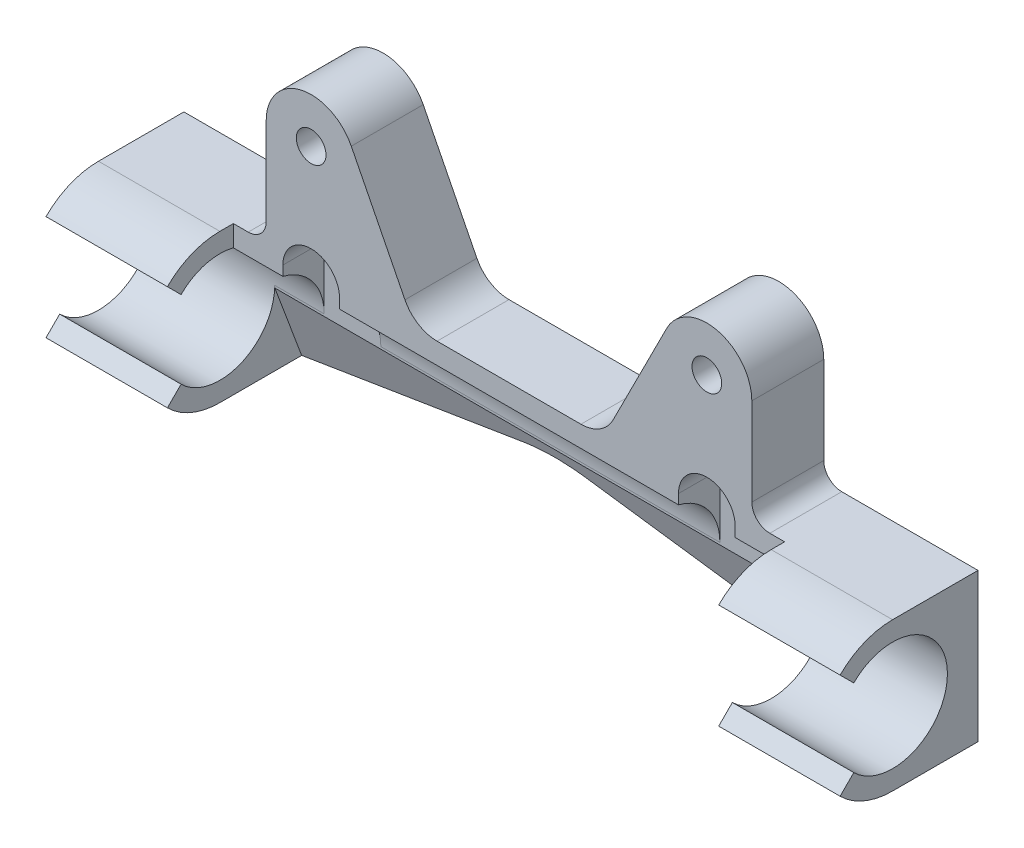
SolidWorks part; units mm, degrees
ref_plane "Front Plane" through (0, 0, 0) normal (0, 0, 1) x (1, 0, 0)
ref_plane "Top Plane" through (0, 0, 0) normal (0, 1, 0) x (1, 0, 0)
ref_plane "Right Plane" through (0, 0, 0) normal (1, 0, 0) x (0, 0, -1)
sketch "Sketch1" plane through (0, 0, 0) normal (-1, 0, 0) x (0, 0, 1)
  line L0 (-9.5, 8.25) -> (-9.5, -8.25)
  line L1 (0, 8.25) -> (-9.5, 8.25)
  line L2 (0, -8.25) -> (-9.5, -8.25)
  arc A4 (0, -8.25) -> (0, 8.25) centre (0, 0) ccw
  dimension "D2" = 16.5
  dimension "D3" = 9.5
extrude "Boss-Extrude1" add sketch "Sketch1" along normal blind 88.3
hole_wizard "Ø2.7 (2.7) Diameter Hole1" [suppressed] positions "Sketch5" profile "Sketch4" hole size "Ø2.7" standard "Ansi Metric"
sketch "Sketch5" [suppressed] plane through (-9.5, 0, 0) normal (-1, 0, 0) x (0, 0, 1)
  line L1 (2.5, -5) -> (11, -5) construction
  line L2 (2.5, -5) -> (2.5, 5) construction
  line L3 (2.5, 5) -> (11, 5) construction
  line L4 (11, -5) -> (11, 5) construction
  line L5 (0, 0) -> (2.5, 0) construction
  line L7 (-8.25, 0) -> (8.25, 0) construction
  line L10 (13.5, 0) -> (11, 0) construction
  line L11 (-8.25, 13.5) -> (8.25, 13.5) construction
  point P0 (2.5, -5)
  point P89 (2.5, 5)
  point P91 (11, 5)
  point P93 (11, -5)
  dimension "D1" = 2.5
  dimension "D2" = 10
sketch "Sketch4" plane through (-9.5, -5, 2.5) normal (0, 1, 0) x (0, 0, 1)
  line L0 (0, 0) -> (0, 4.8112)
  line L1 (0, 4.8112) -> (1.35, 4)
  line L2 (1.35, 4) -> (1.35, 0)
  line L5 (1.35, 0) -> (0, 0)
  line L10 (0, 4.8112) -> (-1.35, 4) construction
  line L11 (0, -6.35) -> (0, 107.95) construction
  dimension "Hole Dia." = 2.7
  dimension "Hole Depth" = 4
  dimension "Drill Angle" = 118
sketch "Sketch6" plane through (0, 0, -9.5) normal (0, 0, -1) x (-1, 0, 0)
  line L0 (44.15, -8.25) -> (44.15, 27.1722) construction
  line L1 (88.3, -8.25) -> (0, -8.25) construction
  line L3 (17.15, -8.25) -> (17.15, 20)
  line L4 (26.6127, 22.2549) -> (32.5796, 10.4461)
  line L5 (17.15, -8.25) -> (71.15, -8.25)
  line L7 (36.1497, 8.25) -> (52.1503, 8.25)
  line L8 (88.3, 8.25) -> (0, 8.25) construction
  line L10 (61.6873, 22.2549) -> (55.7204, 10.4461)
  line L11 (71.15, -8.25) -> (71.15, 20)
  circle A0 centre (22.15, 20) radius 1.65
  arc A2 (26.6127, 22.2549) -> (17.15, 20) centre (22.15, 20) ccw
  arc A3 (32.5796, 10.4461) -> (36.1497, 8.25) centre (36.1497, 12.25) ccw
  arc A4 (55.7204, 10.4461) -> (52.1503, 8.25) centre (52.1503, 12.25) cw
  arc A5 (61.6873, 22.2549) -> (71.15, 20) centre (66.15, 20) cw
  circle A7 centre (66.15, 20) radius 1.65
  point P28 (44.15, 8.25)
  dimension "D4" = 20
  dimension "D5" = 5
  dimension "D6" = 4
extrude "Boss-Extrude2" add sketch "Sketch6" against normal blind 8
sketch "Sketch7" plane through (-88.3, 0, 0) normal (-1, 0, 0) x (0, 0, 1)
  line L0 (13.4819, 13.4819) -> (4.3134, 4.3134)
  line L1 (4.3134, -4.3134) -> (13.4819, -13.4819)
  line L2 (13.4819, -13.4819) -> (13.4819, 13.4819)
  line L3 (0, 0) -> (4.3134, 4.3134) construction
  line L4 (0, 0) -> (4.3134, -4.3134) construction
  arc A0 (4.3134, 4.3134) -> (4.3134, -4.3134) centre (0, 0) ccw
  dimension "D1" = 6.1
extrude "Cut-Extrude1" cut sketch "Sketch7" against normal through all
sketch "Sketch8" plane through (0, 0, -1.5) normal (0, 0, 1) x (1, 0, 0)
  line L0 (-88.3, 8.25) -> (0, 8.25) construction
  line L1 (-74.8, -13.234) -> (-13.5, -13.234)
  line L2 (-74.8, -13.234) -> (-74.8, 8.25)
  line L3 (-74.8, 8.25) -> (-13.5, 8.25)
  line L4 (-13.5, -13.234) -> (-13.5, 8.25)
  line L5 (-88.3, 6.1) -> (-88.3, -6.1) construction
  dimension "D1" = 13.5
  dimension "D2" = 13.5
extrude "Cut-Extrude2" cut sketch "Sketch8" along normal through all
ref_plane "Plane1" through (0, 0, -6.1) normal (0, 0, -1) x (-1, 0, 0)
sketch "Sketch9" plane through (0, 0, -6.1) normal (0, 0, -1) x (-1, 0, 0)
  line L1 (13.5, 0) -> (74.8, 0)
  line L2 (13.5, 0) -> (13.5, -11.6994)
  line L3 (13.5, -11.6994) -> (74.8, -11.6994)
  line L4 (74.8, 0) -> (74.8, -11.6994)
extrude "Cut-Extrude3" cut sketch "Sketch9" against normal through all
sketch "Sketch10" plane through (0, 0, -9.5) normal (0, 0, -1) x (-1, 0, 0)
  line L0 (22.15, 7) -> (66.15, 7) construction
  line L1 (44.15, 7) -> (44.15, -8.25) construction
  line L2 (88.3, -8.25) -> (0, -8.25) construction
  circle A0 centre (22.15, 7) radius 1.65
  circle A1 centre (66.15, 7) radius 1.65
  circle A2 centre (22.15, 20) radius 1.65 construction
  dimension "D2" = 3.3
  dimension "D1" = 44
  dimension "D3" = 13
extrude "Cut-Extrude4" cut sketch "Sketch10" against normal through all
chamfer "Chamfer1" distance 8 distance2 3 1 edges at (-44.15, -8.25, -6.1)
sketch "Sketch11" plane through (0, 0, -6.1) normal (0, 0, -1) x (-1, 0, 0)
  line L0 (74.8, -8.25) -> (47.5959, -1.8288)
  line L2 (40.7041, -1.8288) -> (13.5, -8.25)
  line L3 (13.5, -8.25) -> (13.5, -16.4277)
  line L4 (13.5, -16.4277) -> (74.8, -16.4277)
  line L5 (74.8, -16.4277) -> (74.8, -8.25)
  arc A0 (40.7041, -1.8288) -> (47.5959, -1.8288) centre (44.15, -16.4277) cw
  dimension "D1" = 15
extrude "Cut-Extrude5" cut sketch "Sketch11" along normal through all
fillet "Fillet1" radius 2 2 edges at (-71.15, 8.25, -5.5) (-17.15, 8.25, -5.5)
sketch "Sketch12" plane through (0, 0, -9.5) normal (0, 0, -1) x (-1, 0, 0)
  line L1 (22.15, 16.6514) -> (25.05, 18.3257)
  line L2 (25.05, 18.3257) -> (25.05, 21.6743)
  line L3 (25.05, 21.6743) -> (22.15, 23.3486)
  line L4 (22.15, 23.3486) -> (19.25, 21.6743)
  line L5 (19.25, 21.6743) -> (19.25, 18.3257)
  line L6 (19.25, 18.3257) -> (22.15, 16.6514)
  line L7 (66.15, 16.6514) -> (69.05, 18.3257)
  line L8 (69.05, 18.3257) -> (69.05, 21.6743)
  line L9 (69.05, 21.6743) -> (66.15, 23.3486)
  line L10 (66.15, 23.3486) -> (63.25, 21.6743)
  line L11 (63.25, 21.6743) -> (63.25, 18.3257)
  line L12 (63.25, 18.3257) -> (66.15, 16.6514)
  circle A0 centre (22.15, 20) radius 2.9 construction
  circle A1 centre (66.15, 20) radius 2.9 construction
  circle A2 centre (22.15, 20) radius 1.65 construction
  circle A3 centre (66.15, 20) radius 1.65 construction
  dimension "D1" = 5.8
extrude "Cut-Extrude6" cut sketch "Sketch12" against normal blind 3
sketch "Sketch13" plane through (0, 0, -1.5) normal (0, 0, 1) x (1, 0, 0)
  line L0 (-69.3, 7) -> (-69.3, -2.124)
  line L1 (-69.3, -2.124) -> (-63, -2.124)
  line L2 (-63, -2.124) -> (-63, 7)
  line L3 (-25.3, 7) -> (-25.3, -2.124)
  line L4 (-25.3, -2.124) -> (-19, -2.124)
  line L5 (-19, -2.124) -> (-19, 7)
  arc A0 (-63, 7) -> (-69.3, 7) centre (-66.15, 7) ccw
  arc A1 (-19, 7) -> (-25.3, 7) centre (-22.15, 7) ccw
  arc A2 (-64.9089, 5.9127) -> (-67.3911, 5.9127) centre (-66.15, 7) ccw construction
  arc A3 (-20.9089, 5.9127) -> (-23.3911, 5.9127) centre (-22.15, 7) ccw construction
  dimension "D1" = 6.3
extrude "Cut-Extrude7" cut sketch "Sketch13" against normal up to surface (4.6 mm away)
